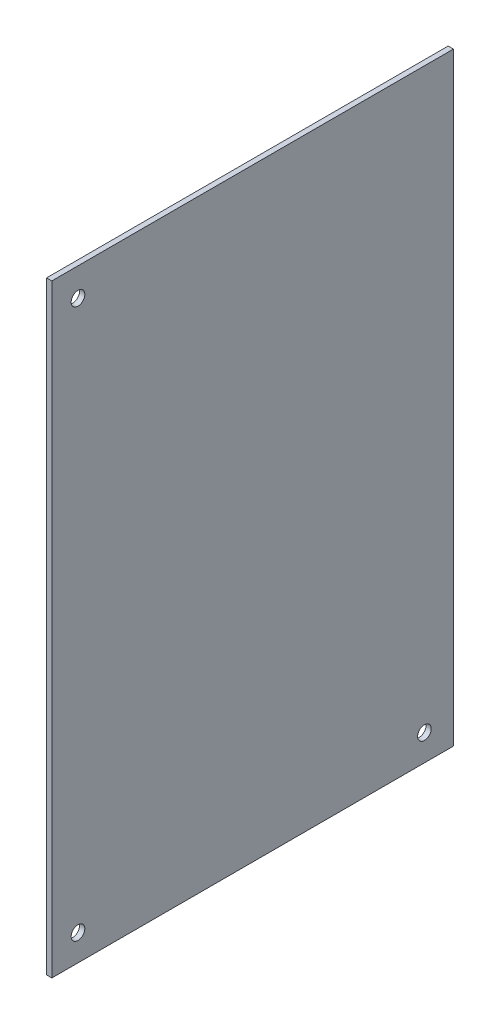
SolidWorks part; units mm, degrees
material "3.1645 (EN AW-2007)"
ref_plane "Přední rovina" through (0, 0, 0) normal (0, 0, 1) x (1, 0, 0)
ref_plane "Horní rovina" through (0, 0, 0) normal (0, 1, 0) x (1, 0, 0)
ref_plane "Pravá rovina" through (0, 0, 0) normal (1, 0, 0) x (0, 0, -1)
sketch "Skica1" plane through (0, 0, 0) normal (1, 0, 0) x (0, 0, -1)
  line L1 (76.5, -115) -> (-76.5, -115)
  line L2 (76.5, -115) -> (76.5, 115)
  line L3 (76.5, 115) -> (-76.5, 115)
  line L4 (-76.5, -115) -> (-76.5, 115)
  line L5 (76.5, -115) -> (-76.5, 115) construction
  line L6 (76.5, 115) -> (-76.5, -115) construction
  point P0 (0, 0)
  dimension "D1" = 153
  dimension "D2" = 230
extrude "Přidat vysunutím1" add sketch "Skica1" along normal blind 2
sketch "Skica2" plane through (2, 0, 0) normal (1, 0, 0) x (0, 0, -1)
  line L0 (71.4, -105) -> (59.5, -105) construction
  line L1 (-66.5, -107.2) -> (-66.5309, -105) construction
  arc A0 (68.7, -107.7) -> (68.7, -102.3) centre (68.7, -105) ccw construction
  arc A1 (62.2, -102.3) -> (62.2, -107.7) centre (62.2, -105) ccw construction
  circle A2 centre (65.45, -105) radius 2.6
  circle A3 centre (-66.5309, -105) radius 2.6
  circle A4 centre (-66.5309, 104.2883) radius 2.6
  dimension "D1" = 5.2
  dimension "D2" = 5.2
extrude "Odebrat vysunutím1" cut sketch "Skica2" against normal blind 2
